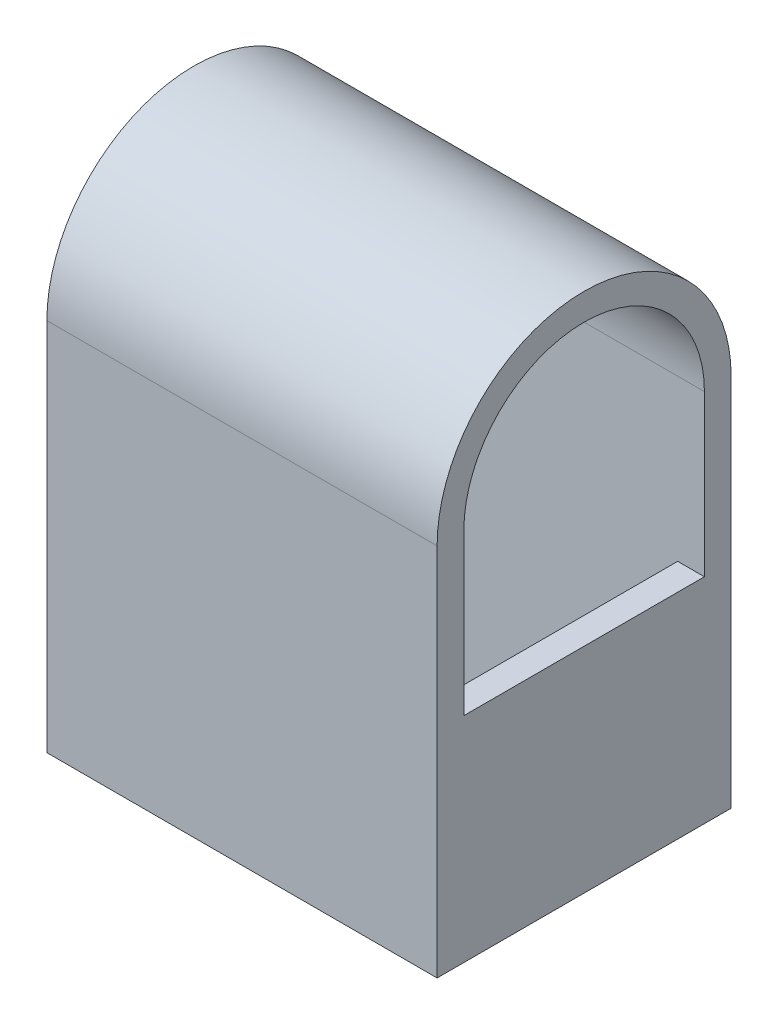
SolidWorks part; units mm, degrees
ref_plane "Front Plane" through (0, 0, 0) normal (0, 0, 1) x (1, 0, 0)
ref_plane "Top Plane" through (0, 0, 0) normal (0, 1, 0) x (1, 0, 0)
ref_plane "Right Plane" through (0, 0, 0) normal (1, 0, 0) x (0, 0, -1)
sketch "Sketch1" plane through (0, 0, 0) normal (0, 0, 1) x (1, 0, 0)
  line L1 (-9.271, -8.89) -> (9.271, -8.89)
  line L2 (-9.271, -8.89) -> (-9.271, 8.89)
  line L3 (-9.271, 8.89) -> (9.271, 8.89)
  line L4 (9.271, -8.89) -> (9.271, 8.89)
  line L5 (-9.271, -8.89) -> (9.271, 8.89) construction
  line L6 (-9.271, 8.89) -> (9.271, -8.89) construction
  point P0 (0, 0)
  dimension "D1" = 17.78
  dimension "D2" = 18.542
ref_plane "Plane2" through (0, 0, -13.97) normal (0, 0, 1) x (1, 0, 0)
sketch "Sketch4" plane through (0, 0, -13.97) normal (0, 0, 1) x (1, 0, 0)
  line L1 (9.271, -8.89) -> (-9.271, -8.89)
  line L2 (9.271, -8.89) -> (9.271, 8.89)
  line L3 (9.271, 8.89) -> (-9.271, 8.89)
  line L4 (-9.271, -8.89) -> (-9.271, 8.89)
  line L5 (9.271, -8.89) -> (-9.271, 8.89) construction
  line L6 (9.271, 8.89) -> (-9.271, -8.89) construction
  point P0 (0, 0)
extrude "Boss-Extrude4" add sketch "Sketch1" against normal blind 1.27
extrude "Boss-Extrude5" add sketch "Sketch4" along normal blind 1.27 separate body
ref_plane "Plane3" through (0, 0, -6.985) normal (0, 0, 1) x (1, 0, 0)
ref_plane "Plane4" through (0, 8.89, 0) normal (0, 1, 0) x (1, 0, 0)
ref_plane "Plane5" through (-9.271, 0, 0) normal (-1, 0, 0) x (0, 0, 1)
sketch "Sketch6" plane through (-9.271, 0, 0) normal (-1, 0, 0) x (0, 0, 1)
  line L0 (-13.97, 0) -> (0, 0) construction
  line L1 (-13.97, -7.454) -> (-13.97, 7.454) construction
  line L2 (-1.27, 8.89) -> (-1.27, -8.89) construction
  line L3 (10.1981, 8.89) -> (-10.1981, 8.89) construction
  line L4 (-6.985, 8.89) -> (-6.35, 7.62) construction
  line L5 (-12.7, 8.89) -> (-13.97, 8.89) construction
  line L6 (-13.97, 8.89) -> (-12.7, 8.89)
  line L7 (-1.27, 8.89) -> (0, 8.89)
  arc A0 (-12.7, 8.89) -> (-1.27, 8.89) centre (-6.985, 8.89) cw
  arc A1 (0, 8.89) -> (-13.97, 8.89) centre (-6.985, 8.89) ccw
extrude "Boss-Extrude6" add sketch "Sketch6" against normal up to surface (18.542 mm away) up to face at (9.271, 0, -0.635)
sketch "Sketch7" plane through (-9.271, 0, 0) normal (-1, 0, 0) x (0, 0, 1)
  line L0 (-1.27, 8.89) -> (-1.27, -8.89) construction
  line L1 (-12.7, -8.89) -> (-1.27, -8.89)
  line L2 (-12.7, -8.89) -> (-12.7, 1.27)
  line L3 (-12.7, 1.27) -> (-1.27, 1.27)
  line L4 (-1.27, -8.89) -> (-1.27, 1.27)
  dimension "D1" = 10.16
extrude "Boss-Extrude7" add sketch "Sketch7" against normal blind 1.27
ref_plane "Plane8" through (0, 0, 0) normal (-1, 0, 0) x (0, 0, 1)
ref_plane "Plane9" through (9.271, 0, 0) normal (1, 0, 0) x (0, 0, -1)
sketch "Sketch8" plane through (9.271, 0, 0) normal (1, 0, 0) x (0, 0, -1)
  line L1 (1.905, 1.27) -> (1.27, 1.27)
  line L2 (1.27, -8.89) -> (1.27, 8.89) construction
  line L3 (1.27, 1.27) -> (1.27, -8.89)
  line L7 (1.905, 1.27) -> (10.795, 1.27)
  line L10 (12.7, -8.89) -> (12.7, 1.27)
  line L11 (12.7, -8.89) -> (12.7, 8.89) construction
  line L12 (10.795, 1.27) -> (12.7, 1.27)
  line L13 (1.27, -8.89) -> (12.7, -8.89)
sketch "Sketch12" plane through (0, 0, -13.97) normal (0, 0, -1) x (-1, 0, 0)
  line L4 (0, -8.89) -> (0, 0) construction
  line L5 (-6.35, -8.89) -> (6.35, -8.89) construction
  line L7 (6.35, -8.89) -> (-6.35, -8.89)
  line L8 (-6.35, -8.89) -> (-6.35, 3.81)
  line L9 (-6.35, 3.81) -> (6.35, 3.81)
  line L10 (6.35, 3.81) -> (6.35, -8.89)
extrude "Boss-Extrude11" add sketch "Sketch12" along normal blind 2.286
sketch "Sketch13" plane through (0, 3.81, 0) normal (0, 1, 0) x (1, 0, 0)
  line L0 (0, 16.256) -> (0, 13.97) construction
  line L1 (-6.35, 16.256) -> (6.35, 16.256) construction
  line L2 (-5.0332, 13.97) -> (5.0332, 13.97) construction
  line L3 (5.08, 13.97) -> (-5.08, 13.97) construction
  line L4 (-6.35, 13.97) -> (6.35, 13.97) construction
  line L5 (-5.08, 13.97) -> (5.08, 13.97)
  line L6 (5.08, 13.97) -> (5.08, 15.4933)
  line L7 (5.08, 15.4933) -> (-5.08, 15.748)
  line L8 (-5.08, 15.748) -> (-5.08, 13.97)
extrude "Cut-Extrude2" cut sketch "Sketch13" against normal through all
extrude "Boss-Extrude12" add sketch "Sketch8" against normal blind 1.27
